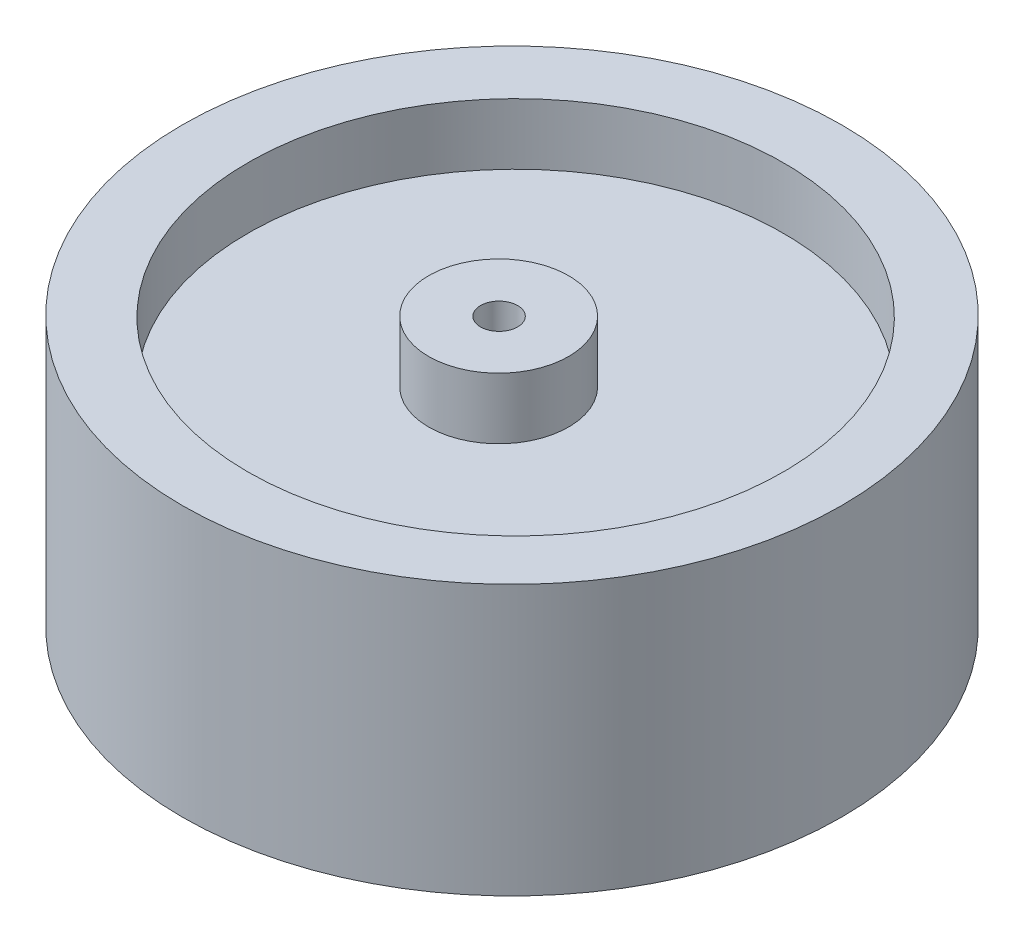
SolidWorks part; units mm, degrees
ref_plane "Front Plane" through (0, 0, 0) normal (0, 0, 1) x (1, 0, 0)
ref_plane "Top Plane" through (0, 0, 0) normal (0, 1, 0) x (1, 0, 0)
ref_plane "Right Plane" through (0, 0, 0) normal (1, 0, 0) x (0, 0, -1)
sketch "Sketch1" plane through (0, 0, 0) normal (0, 1, 0) x (1, 0, 0)
  circle A0 centre (3.1895, 0) radius 32.5
extrude "Boss-Extrude1" add sketch "Sketch1" along normal blind 26.6 contours A0
sketch "Sketch2" plane through (0, 26.6, 0) normal (0, 1, 0) x (1, 0, 0)
  circle A0 centre (3.5479, 0) radius 26.4
extrude "Cut-Extrude1" cut sketch "Sketch2" against normal blind 6.026
sketch "Sketch5" plane through (0, 0, 0) normal (0, -1, 0) x (1, 0, 0)
  circle A0 centre (2.9206, 0) radius 25.9
extrude "Cut-Extrude2" cut sketch "Sketch5" against normal blind 15.932
sketch "Sketch6" plane through (0, 20.574, 0) normal (0, 1, 0) x (1, 0, 0)
  circle A0 centre (2.6052, -0.7323) radius 6.9
extrude "Boss-Extrude2" add sketch "Sketch6" along normal blind 6.026 and the other way blind 20.828
sketch "Sketch7" plane through (0, 26.6, 0) normal (0, 1, 0) x (1, 0, 0)
  circle A0 centre (2.6414, -0.7242) radius 1.83
extrude "Cut-Extrude3" cut sketch "Sketch7" against normal blind 49.714 and the other way blind 13.462
